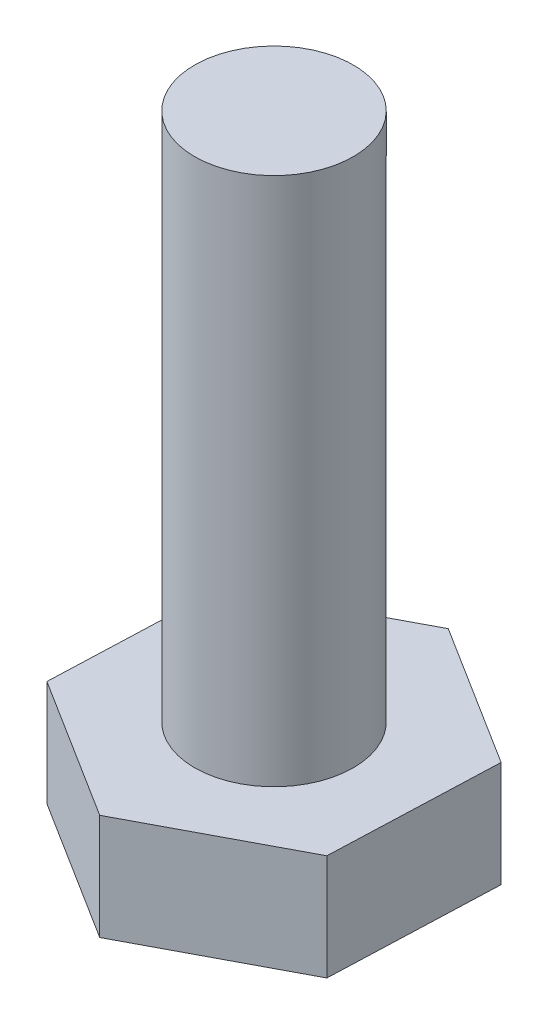
SolidWorks part; units mm, degrees
material "POM Acetal Copolymer"
ref_plane "Front Plane" through (0, 0, 0) normal (0, 0, 1) x (1, 0, 0)
ref_plane "Top Plane" through (0, 0, 0) normal (0, 1, 0) x (1, 0, 0)
ref_plane "Right Plane" through (0, 0, 0) normal (1, 0, 0) x (0, 0, -1)
sketch "Sketch1" plane through (0, 0, 0) normal (0, 1, 0) x (1, 0, 0)
  line L1 (-9.0005, -6.2612) -> (-8.2518, -3.1753)
  line L2 (-8.2518, -3.1753) -> (-10.5499, -0.9839)
  line L3 (-10.5499, -0.9839) -> (-13.5967, -1.8784)
  line L4 (-13.5967, -1.8784) -> (-14.3454, -4.9643)
  line L5 (-14.3454, -4.9643) -> (-12.0474, -7.1557)
  line L6 (-12.0474, -7.1557) -> (-9.0005, -6.2612)
  circle A0 centre (-11.2986, -4.0698) radius 2.75 construction
  circle A1 centre (-11.2986, -4.0698) radius 1.5
extrude "Boss-Extrude1" add sketch "Sketch1" along normal blind 8 and the other way blind 2 contours A1
sketch "Sketch2" plane through (0, -2, 0) normal (0, -1, 0) x (1, 0, 0)
  line L1 (-14.1064, 5.5529) -> (-13.9869, 2.3797)
  line L2 (-13.9869, 2.3797) -> (-11.1791, 0.8966)
  line L3 (-11.1791, 0.8966) -> (-8.4908, 2.5867)
  line L4 (-8.4908, 2.5867) -> (-8.6103, 5.7598)
  line L5 (-8.6103, 5.7598) -> (-11.4181, 7.243)
  line L6 (-11.4181, 7.243) -> (-14.1064, 5.5529)
  circle A0 centre (-11.2986, 4.0698) radius 1.5
  circle A1 centre (-11.2986, 4.0698) radius 2.75 construction
extrude "Boss-Extrude2" add sketch "Sketch2" along normal blind 2 separate body
sketch "Sketch5" plane through (0, -4, 0) normal (0, -1, 0) x (1, 0, 0)
  circle A0 centre (-11.2986, 4.0698) radius 1.5
extrude "Boss-Extrude3" add sketch "Sketch5" against normal blind 2
